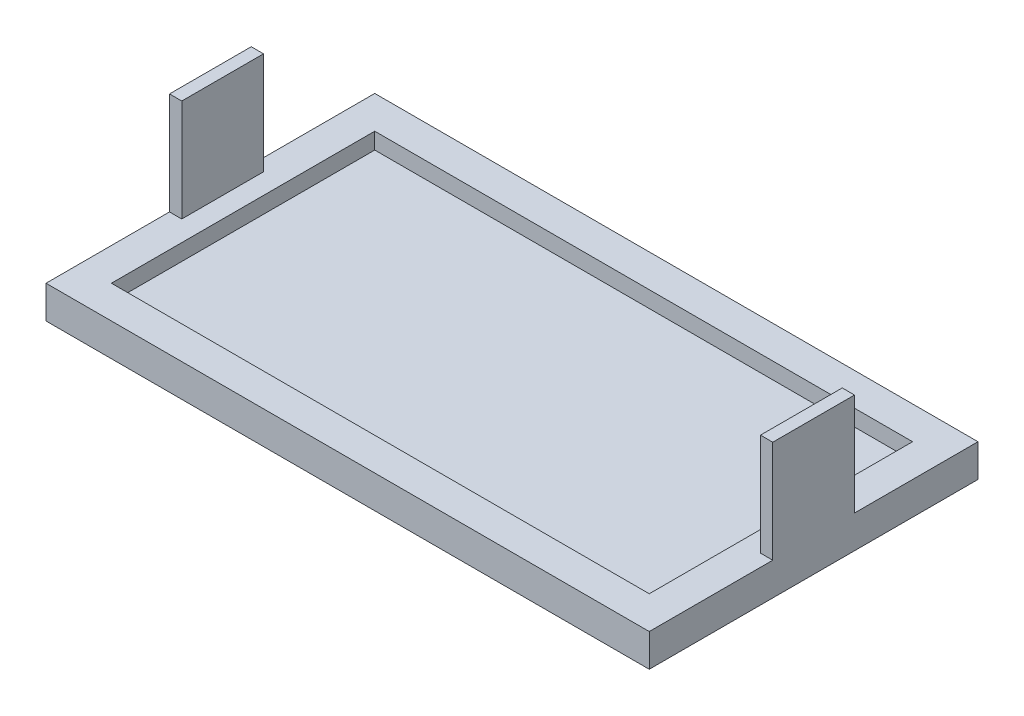
SolidWorks part; units mm, degrees
ref_plane "Front Plane" through (0, 0, 0) normal (0, 0, 1) x (1, 0, 0)
ref_plane "Top Plane" through (0, 0, 0) normal (0, 1, 0) x (1, 0, 0)
ref_plane "Right Plane" through (0, 0, 0) normal (1, 0, 0) x (0, 0, -1)
sketch "Sketch1" plane through (0, 0, 0) normal (0, 1, 0) x (1, 0, 0)
  line L1 (0, 0) -> (147.57, 0)
  line L2 (0, 0) -> (0, 80.42)
  line L3 (0, 80.42) -> (147.57, 80.42)
  line L4 (147.57, 0) -> (147.57, 80.42)
  line L5 (0, 0) -> (147.57, 80.42) construction
  line L6 (0, 80.42) -> (147.57, 0) construction
  point P4 (73.785, 40.21)
  dimension "D1" = 147.57
  dimension "D2" = 80.42
extrude "Boss-Extrude1" add sketch "Sketch1" along normal blind 8
sketch "Sketch2" plane through (0, 8, 0) normal (0, 1, 0) x (1, 0, 0)
  line L0 (0, 80.42) -> (0, 0) construction
  line L1 (8, 72.42) -> (139.57, 72.42)
  line L2 (8, 72.42) -> (8, 8)
  line L3 (8, 8) -> (139.57, 8)
  line L4 (139.57, 72.42) -> (139.57, 8)
  line L5 (8, 72.42) -> (139.57, 8) construction
  line L6 (8, 8) -> (139.57, 72.42) construction
  line L7 (147.57, 0) -> (147.57, 80.42) construction
  line L8 (147.57, 80.42) -> (0, 80.42) construction
  line L9 (0, 0) -> (147.57, 0) construction
  point P4 (73.785, 40.21)
  dimension "D1" = 8
  dimension "D2" = 8
  dimension "D3" = 8
  dimension "D4" = 8
extrude "Cut-Extrude1" cut sketch "Sketch2" against normal blind 4
sketch "Sketch3" plane through (0, 8, 0) normal (0, 1, 0) x (1, 0, 0)
  line L0 (0, 80.42) -> (0, 0) construction
  line L1 (0, 50.21) -> (3, 50.21)
  line L2 (0, 50.21) -> (0, 30.21)
  line L3 (0, 30.21) -> (3, 30.21)
  line L4 (3, 50.21) -> (3, 30.21)
  line L5 (0, 50.21) -> (3, 30.21) construction
  line L6 (0, 30.21) -> (3, 50.21) construction
  line L7 (147.57, 80.42) -> (0, 80.42) construction
  point P4 (1.5, 40.21)
  dimension "D1" = 40.21
  dimension "D2" = 20
  dimension "D3" = 3
extrude "Boss-Extrude2" add sketch "Sketch3" along normal blind 25
sketch "Sketch4" plane through (0, 8, 0) normal (0, 1, 0) x (1, 0, 0)
  line L0 (73.785, 80.42) -> (73.785, 0) construction
  line L1 (147.57, 80.42) -> (0, 80.42) construction
  line L2 (0, 0) -> (147.57, 0) construction
ref_plane "Plane1" through (73.785, 0, 0) normal (-1, 0, 0) x (0, 0, 1)
mirror "Mirror1" about plane through (73.785, 0, 0) normal (-1, 0, 0) of "Boss-Extrude2"
sketch "Sketch5" plane through (0, 0, 0) normal (-1, 0, 0) x (0, 0, 1)
  line L0 (-40.21, 33) -> (-40.21, 28) construction
  line L1 (-50.21, 33) -> (-30.21, 33) construction
  dimension "D1" = 5
hole_wizard "#4 (0.209) Diameter Hole1" positions "3DSketch1" profile "Sketch6" hole size "#4" standard "ANSI Inch"
sketch3d "3DSketch1"
  point P0 (0, 28, -40.21)
sketch "Sketch6" plane through (0, 28, -40.21) normal (0, 1, 0) x (0, 0, 1)
  line L0 (0, 0) -> (0, 147.57)
  line L1 (0, 147.57) -> (2.6543, 147.57)
  line L2 (2.6543, 147.57) -> (2.6543, 0)
  line L5 (2.6543, 0) -> (0, 0)
  line L11 (0, -6.35) -> (0, 107.95) construction
  dimension "Thru Hole Dia." = 5.3086
  dimension "Thru Hole Depth" = 147.57
